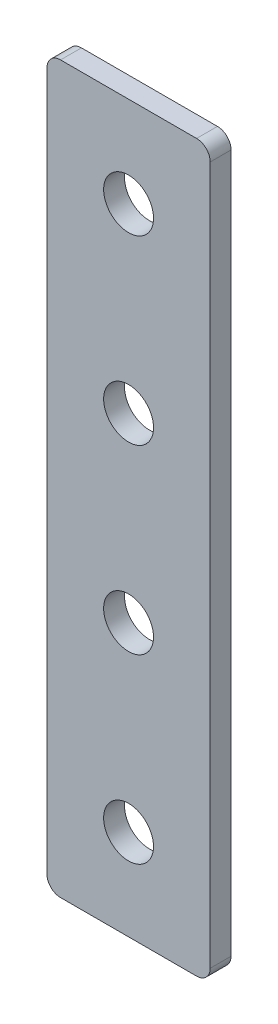
SolidWorks part; units mm, degrees
ref_plane "Front Plane" through (0, 0, 0) normal (0, 0, 1) x (1, 0, 0)
ref_plane "Top Plane" through (0, 0, 0) normal (0, 1, 0) x (1, 0, 0)
ref_plane "Right Plane" through (0, 0, 0) normal (1, 0, 0) x (0, 0, -1)
ref_plane "Plane1" through (0, 0, 0) normal (0, 0, 1) x (1, 0, 0)
sketch "Sketch1" plane through (0, 0, 0) normal (0, 0, 1) x (1, 0, 0)
  line L0 (-7.5, 0) -> (7.5, 0)
  line L1 (9, 1.5) -> (9, 78.5)
  line L2 (7.5, 80) -> (-7.5, 80)
  line L3 (-9, 78.5) -> (-9, 1.5)
  arc A0 (-9, 1.5) -> (-7.5, 0) centre (-7.5, 1.5) ccw
  arc A1 (7.5, 0) -> (9, 1.5) centre (7.5, 1.5) ccw
  arc A2 (9, 78.5) -> (7.5, 80) centre (7.5, 78.5) ccw
  arc A3 (-7.5, 80) -> (-9, 78.5) centre (-7.5, 78.5) ccw
  circle A4 centre (0, 70) radius 2.75
  circle A5 centre (0, 50) radius 2.75
  circle A6 centre (0, 30) radius 2.75
  circle A7 centre (0, 10) radius 2.75
extrude "Boss-Extrude1" add sketch "Sketch1" against normal blind 2.3
